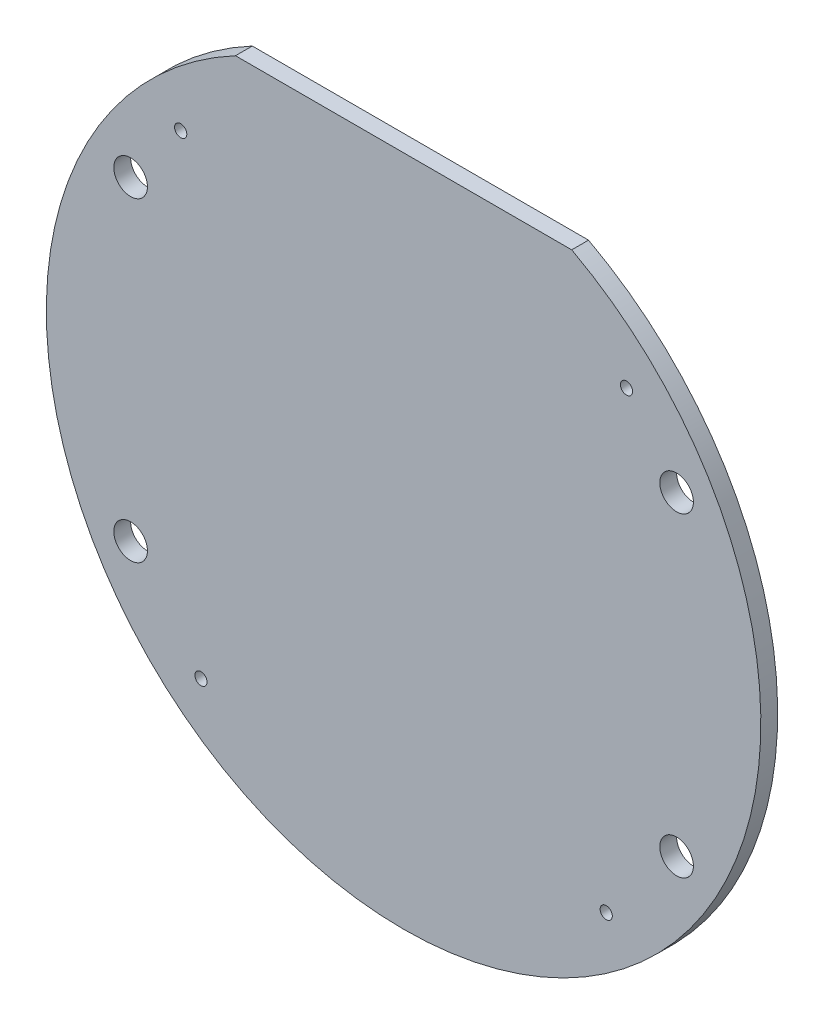
SolidWorks part; units mm, degrees
ref_plane "Plano frontal" through (0, 0, 0) normal (0, 0, 1) x (1, 0, 0)
ref_plane "Plano superior" through (0, 0, 0) normal (0, 1, 0) x (1, 0, 0)
ref_plane "Plano direito" through (0, 0, 0) normal (1, 0, 0) x (0, 0, -1)
sketch "Esboço1" plane through (0, 0, 0) normal (0, 0, 1) x (1, 0, 0)
  line L1 (-40, 75) -> (40, 75)
  arc A0 (-40, 75) -> (40, 75) centre (0, 0) ccw
  point P3 (0, 75)
  point P8 (0, 75)
  dimension "D1" = 170
  dimension "D2" = 75
extrude "Ressalto-extrusão1" add sketch "Esboço1" along normal blind 4
sketch "Esboço2" plane through (0, 0, 4) normal (0, 0, 1) x (1, 0, 0)
  line L0 (-85, 0) -> (0, 0) construction
  line L1 (0, 0) -> (85, 0) construction
  line L2 (0, 0) -> (53.033, 53.033) construction
  line L3 (0, 0) -> (-53.033, 53.033) construction
  line L4 (0, 0) -> (64.9519, 37.5) construction
  line L5 (0, 0) -> (64.9519, -37.5) construction
  line L6 (0, 0) -> (48.2091, -57.4533) construction
  line L7 (0, 0) -> (-64.9519, 37.5) construction
  line L8 (0, 0) -> (-64.9519, -37.5) construction
  line L9 (0, 0) -> (-48.2091, -57.4533) construction
  arc A1 (-40, 75) -> (40, 75) centre (0, 0) ccw construction
  dimension "D1" = 75
  dimension "D2" = 45
  dimension "D3" = 30
  dimension "D4" = 30
  dimension "D5" = 50
  dimension "D6" = 75
  dimension "D7" = 45
  dimension "D8" = 30
  dimension "D9" = 30
  dimension "D10" = 50
hole_wizard "Furo com folga de M2.51" positions "3DSketch2" profile "Esboço4" hole size "M2.5" standard "ISO"
sketch3d "3DSketch2"
  point P0 (-53.033, 53.033, 4)
  point P3 (53.033, 53.033, 4)
  point P6 (48.2091, -57.4533, 4)
  point P9 (-48.2091, -57.4533, 4)
sketch "Esboço4" plane through (-53.033, 53.033, 4) normal (1, 0, 0) x (0, -1, 0)
  line L0 (0, 0) -> (0, 8.1212)
  line L1 (0, 8.1212) -> (1.45, 7.25)
  line L2 (1.45, 7.25) -> (1.45, 0)
  line L5 (1.45, 0) -> (0, 0)
  line L10 (0, 8.1212) -> (-1.45, 7.25) construction
  line L11 (0, -6.35) -> (0, 107.95) construction
  dimension "Hole Dia." = 2.9
  dimension "Hole Depth" = 7.25
  dimension "Drill Angle" = 118
hole_wizard "Furos-guia com Ø8.0mm1" positions "3DSketch3" profile "Esboço5" hole size "Ø8.0" standard "ISO"
sketch3d "3DSketch3"
  point P0 (-64.9519, 37.5, 4)
  point P3 (-64.9519, -37.5, 4)
  point P6 (64.9519, 37.5, 4)
  point P9 (64.9519, -37.5, 4)
sketch "Esboço5" plane through (-64.9519, 37.5, 4) normal (1, 0, 0) x (0, -1, 0)
  line L0 (0, 0) -> (0, 9.6534)
  line L1 (0, 9.6534) -> (4, 7.25)
  line L2 (4, 7.25) -> (4, 0)
  line L5 (4, 0) -> (0, 0)
  line L10 (0, 9.6534) -> (-4, 7.25) construction
  line L11 (0, -6.35) -> (0, 107.95) construction
  dimension "Hole Dia." = 8
  dimension "Hole Depth" = 7.25
  dimension "Drill Angle" = 118
